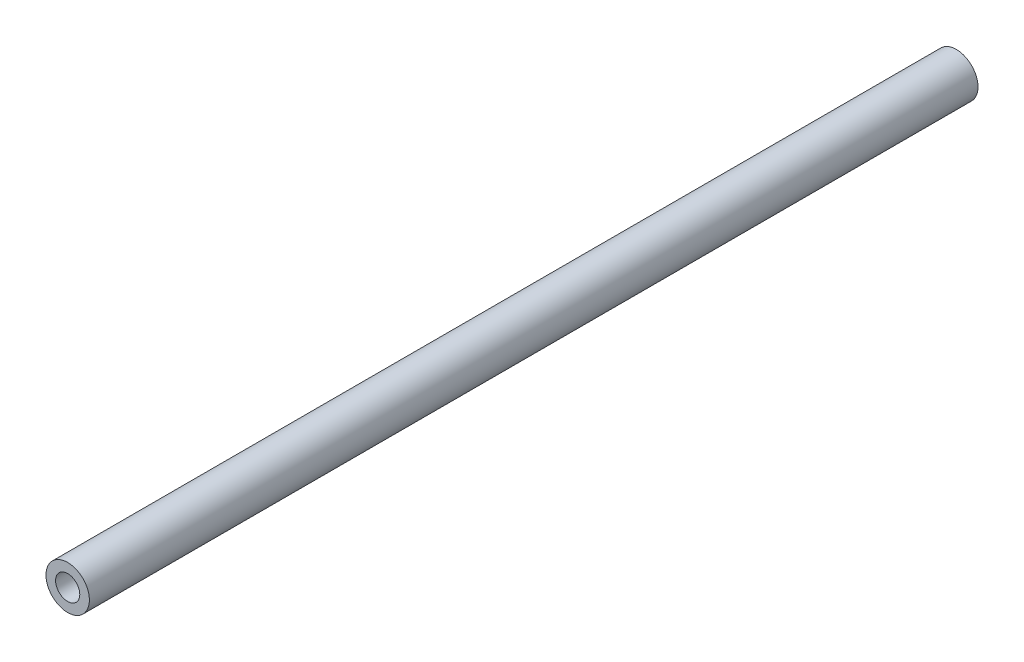
SolidWorks part; units mm, degrees
ref_plane "Front Plane" through (0, 0, 0) normal (0, 0, 1) x (1, 0, 0)
ref_plane "Top Plane" through (0, 0, 0) normal (0, 1, 0) x (1, 0, 0)
ref_plane "Right Plane" through (0, 0, 0) normal (1, 0, 0) x (0, 0, -1)
sketch "Sketch32" plane through (0, 0, 0) normal (0, 0, 1) x (1, 0, 0)
  circle A0 centre (0, 0) radius 8.55
  circle A1 centre (0, 0) radius 4.765
  dimension "D1" = 17.1
  dimension "D2" = 9.53
extrude "Boss-Extrude1" add sketch "Sketch32" along normal blind 350
